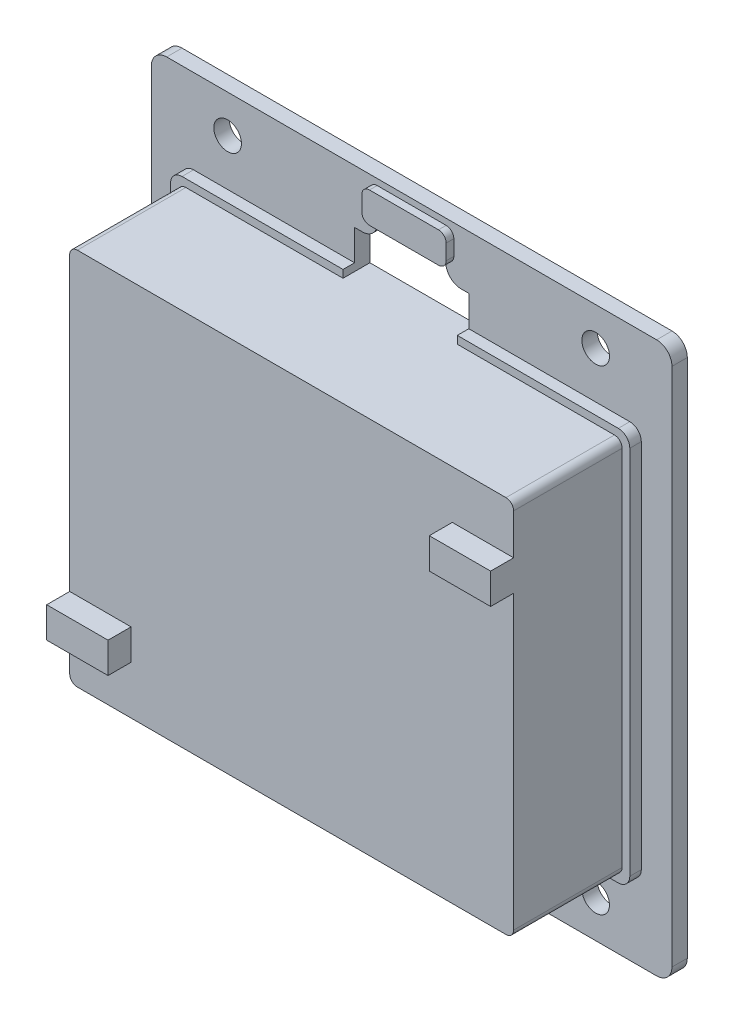
SolidWorks part; units mm, degrees
ref_plane "前视基准面" through (0, 0, 0) normal (0, 0, 1) x (1, 0, 0)
ref_plane "上视基准面" through (0, 0, 0) normal (0, 1, 0) x (1, 0, 0)
ref_plane "右视基准面" through (0, 0, 0) normal (1, 0, 0) x (0, 0, -1)
sketch "草图1" plane through (0, 0, 0) normal (0, 0, 1) x (1, 0, 0)
  line L1 (-33.95, 35.925) -> (33.95, 35.925)
  line L2 (-33.95, 35.925) -> (-33.95, -35.925)
  line L3 (-33.95, -35.925) -> (33.95, -35.925)
  line L4 (33.95, 35.925) -> (33.95, -35.925)
  line L5 (-33.95, 35.925) -> (33.95, -35.925) construction
  line L6 (-33.95, -35.925) -> (33.95, 35.925) construction
  point P0 (0, 0)
  dimension "D1" = 67.9
  dimension "D2" = 71.85
extrude "凸台-拉伸1" add sketch "草图1" along normal blind 2
sketch "草图2" plane through (0, 0, 2) normal (0, 0, 1) x (1, 0, 0)
  line L0 (33.95, 35.925) -> (-33.95, 35.925) construction
  line L1 (-29.95, 24.925) -> (29.95, 24.925)
  line L2 (-29.95, 24.925) -> (-29.95, -26.425)
  line L3 (-29.95, -26.425) -> (29.95, -26.425)
  line L4 (29.95, 24.925) -> (29.95, -26.425)
  line L5 (-33.95, -35.925) -> (33.95, -35.925) construction
  line L6 (33.95, -35.925) -> (33.95, 35.925) construction
  line L7 (-33.95, 35.925) -> (-33.95, -35.925) construction
  dimension "D1" = 11
  dimension "D2" = 9.5
  dimension "D3" = 4
  dimension "D4" = 4
extrude "凸台-拉伸2" add sketch "草图2" along normal blind 1.5
sketch "草图3" plane through (0, 0, 3.5) normal (0, 0, 1) x (1, 0, 0)
  line L0 (29.95, 24.925) -> (-29.95, 24.925) construction
  line L1 (-28.95, 23.925) -> (28.95, 23.925)
  line L2 (-28.95, 23.925) -> (-28.95, -25.425)
  line L3 (-28.95, -25.425) -> (28.95, -25.425)
  line L4 (28.95, 23.925) -> (28.95, -25.425)
  line L5 (29.95, -26.425) -> (29.95, 24.925) construction
  line L6 (-29.95, -26.425) -> (29.95, -26.425) construction
  line L7 (-29.95, 24.925) -> (-29.95, -26.425) construction
  dimension "D1" = 1
  dimension "D2" = 1
  dimension "D3" = 1
  dimension "D4" = 1
extrude "凸台-拉伸3" add sketch "草图3" along normal blind 14.15
sketch "草图4" plane through (0, 0, 0) normal (0, 0, -1) x (-1, 0, 0)
  circle A0 centre (24, 31) radius 1.8
  circle A1 centre (-24, 31) radius 1.8
  circle A2 centre (-24, -31) radius 1.8
  circle A3 centre (24, -31) radius 1.8
  dimension "D1" = 3.6
  dimension "D4" = 3.6
  dimension "D6" = 31
  dimension "D2" = 24
  dimension "D3" = 31
  dimension "D5" = 24
extrude "切除-拉伸1" cut sketch "草图4" against normal through all
fillet "圆角1" radius 2 4 edges at (33.95, -35.925, 1) (-33.95, -35.925, 1) (-33.95, 35.925, 1) (33.95, 35.925, 1)
fillet "圆角2" radius 1.5 4 edges at (-29.95, 24.925, 2.75) (29.95, -26.425, 2.75) (-29.95, -26.425, 2.75) (29.95, 24.925, 2.75)
fillet "圆角3" radius 1 4 edges at (-28.95, -25.425, 10.575) (-28.95, 23.925, 10.575) (28.95, -25.425, 10.575) (28.95, 23.925, 10.575)
sketch "草图6" plane through (0, 0, 0) normal (0, 0, -1) x (-1, 0, 0)
  line L0 (-31.95, 35.925) -> (31.95, 35.925) construction
  line L1 (-4.45, 33.925) -> (4.45, 33.925)
  line L2 (-4.45, 33.925) -> (-4.45, 28.925)
  line L4 (4.45, 33.925) -> (4.45, 28.925)
  line L5 (33.95, 33.925) -> (33.95, -33.925) construction
  line L6 (-33.95, -33.925) -> (-33.95, 33.925) construction
  line L7 (4.45, 28.925) -> (7.45, 28.925)
  line L8 (-7.45, 28.925) -> (-4.45, 28.925)
  line L9 (-7.45, 28.925) -> (-7.45, 23.925)
  line L10 (-7.45, 23.925) -> (7.45, 23.925)
  line L11 (7.45, 28.925) -> (7.45, 23.925)
  dimension "D1" = 2
  dimension "D2" = 29.5
  dimension "D3" = 29.5
  dimension "D5" = 26.5
  dimension "D6" = 26.5
  dimension "D7" = 5
extrude "切除-拉伸2" cut sketch "草图6" against normal through all
fillet "圆角4" radius 2 2 edges at (-4.45, 28.925, 1) (4.45, 28.925, 1)
sketch "草图7" plane through (0, 0, 2) normal (0, 0, 1) x (1, 0, 0)
  line L0 (31.95, 35.925) -> (-31.95, 35.925) construction
  line L1 (-5.5, 35.125) -> (5.5, 35.125)
  line L2 (-5.5, 35.125) -> (-5.5, 31.125)
  line L3 (-5.5, 31.125) -> (5.5, 31.125)
  line L4 (5.5, 35.125) -> (5.5, 31.125)
  point P6 (0, 35.125)
  dimension "D1" = 0.8
  dimension "D2" = 4
  dimension "D3" = 0
  dimension "D4" = 11
extrude "凸台-拉伸4" add sketch "草图7" along normal blind 1
fillet "圆角5" radius 1 4 edges at (-5.5, 31.125, 2.5) (5.5, 31.125, 2.5) (5.5, 35.125, 2.5) (-5.5, 35.125, 2.5)
sketch "草图8" plane through (0, 0, 17.65) normal (0, 0, 1) x (1, 0, 0)
  line L0 (28.95, -24.425) -> (28.95, 22.925) construction
  line L1 (20.95, 17.625) -> (28.95, 17.625)
  line L2 (20.95, 17.625) -> (20.95, 13.625)
  line L3 (20.95, 13.625) -> (28.95, 13.625)
  line L4 (28.95, 17.625) -> (28.95, 13.625)
  line L5 (20.95, 17.625) -> (28.95, 13.625) construction
  line L6 (20.95, 13.625) -> (28.95, 17.625) construction
  line L7 (27.95, 23.925) -> (-27.95, 23.925) construction
  line L8 (-28.95, 22.925) -> (-28.95, -24.425) construction
  line L9 (-20.95, -15.125) -> (-28.95, -15.125)
  line L10 (-20.95, -15.125) -> (-20.95, -19.125)
  line L11 (-20.95, -19.125) -> (-28.95, -19.125)
  line L12 (-28.95, -15.125) -> (-28.95, -19.125)
  line L13 (-20.95, -15.125) -> (-28.95, -19.125) construction
  line L14 (-20.95, -19.125) -> (-28.95, -15.125) construction
  line L15 (-27.95, -25.425) -> (27.95, -25.425) construction
  point P0 (24.95, 15.625)
  point P9 (-24.95, -17.125)
  dimension "D1" = 8.3
  dimension "D2" = 4
  dimension "D3" = 8
  dimension "D4" = 8.3
  dimension "D5" = 4
  dimension "D6" = 8
extrude "凸台-拉伸5" add sketch "草图8" along normal blind 3
